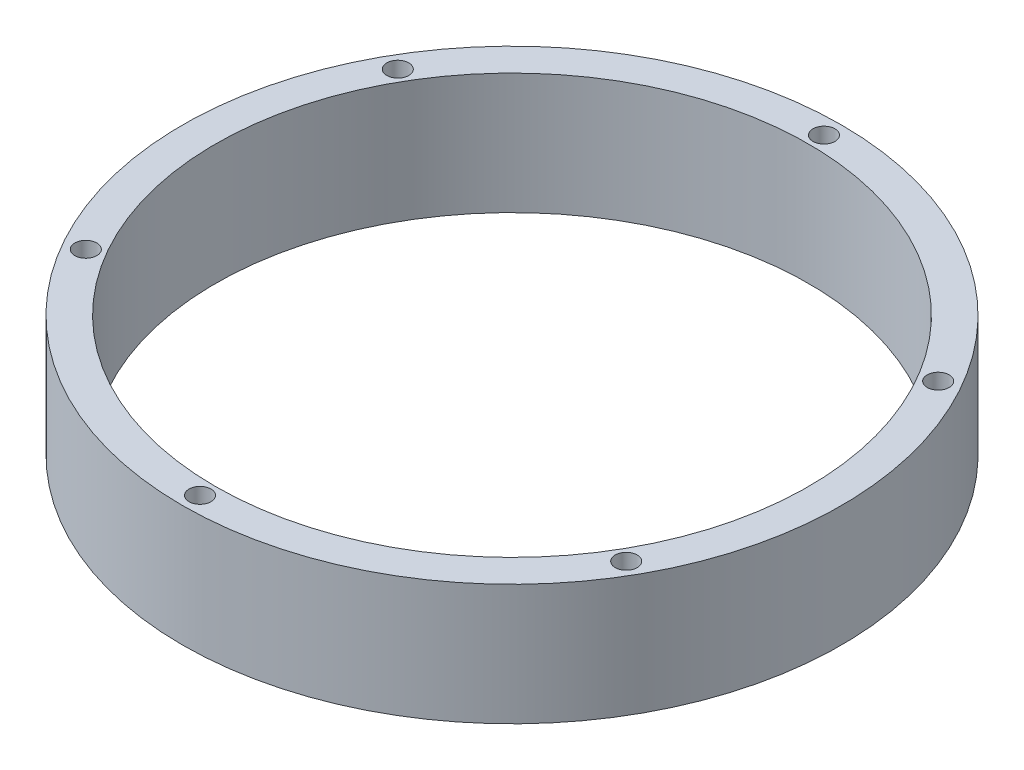
SolidWorks part; units mm, degrees
ref_plane "Front Plane" through (0, 0, 0) normal (0, 0, 1) x (1, 0, 0)
ref_plane "Top Plane" through (0, 0, 0) normal (0, 1, 0) x (1, 0, 0)
ref_plane "Right Plane" through (0, 0, 0) normal (1, 0, 0) x (0, 0, -1)
sketch "Sketch1" plane through (0, 0, 0) normal (0, 1, 0) x (1, 0, 0)
  circle A0 centre (0, 0) radius 15
  circle A1 centre (0, 0) radius 13.5
  dimension "D1" = 30
  dimension "D2" = 27
extrude "Boss-Extrude1" add sketch "Sketch1" along normal blind 5.5
sketch "Sketch2" plane through (0, 5.5, 0) normal (0, 1, 0) x (1, 0, 0)
  circle A0 centre (0, 14.2) radius 0.5
  dimension "D1" = 1
  dimension "D2" = 14.2
extrude "Cut-Extrude1" cut sketch "Sketch2" against normal blind 5.5
pattern_circular "CirPattern1" count 6 over 360 about axis through (0, 0, 0) along (0, 1, 0) of "Cut-Extrude1"
scale "Scale1" scale about centroid uniform scaling yes scale factor 5
